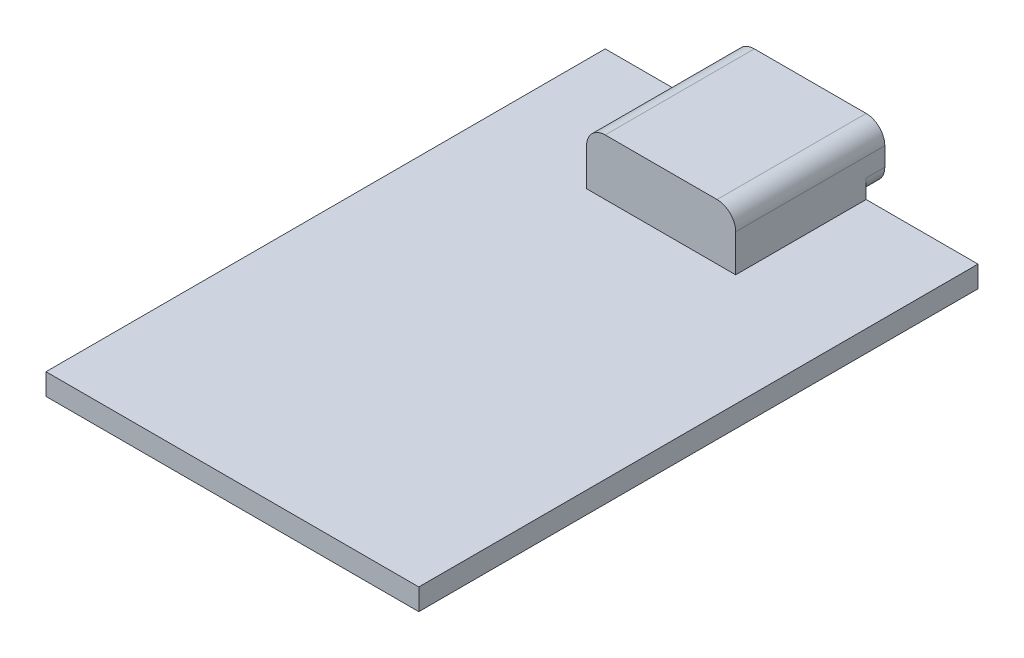
SolidWorks part; units mm, degrees
ref_plane "Alzado" through (0, 0, 0) normal (0, 0, 1) x (1, 0, 0)
ref_plane "Planta" through (0, 0, 0) normal (0, 1, 0) x (1, 0, 0)
ref_plane "Vista lateral" through (0, 0, 0) normal (1, 0, 0) x (0, 0, -1)
sketch "Croquis1" plane through (0, 0, 0) normal (0, 1, 0) x (1, 0, 0)
  line L0 (0, 0) -> (0, 15) construction
  line L1 (-10, 15) -> (10, 15)
  line L2 (-10, 15) -> (-10, -15)
  line L3 (-10, -15) -> (10, -15)
  line L4 (10, 15) -> (10, -15)
  line L5 (-10, 15) -> (10, -15) construction
  line L6 (-10, -15) -> (10, 15) construction
  line L7 (0, 0) -> (-10, 0) construction
  point P0 (0, 0)
  dimension "D1" = 30
  dimension "D2" = 20
extrude "Saliente-Extruir1" add sketch "Croquis1" along normal blind 1.15
sketch "Croquis2" plane through (0, 1.15, 0) normal (0, 1, 0) x (1, 0, 0)
  line L0 (0, 0) -> (0, 12) construction
  line L1 (4, 8) -> (-4, 8)
  line L2 (4, 8) -> (4, 16)
  line L3 (4, 16) -> (-4, 16)
  line L4 (-4, 8) -> (-4, 16)
  line L5 (4, 8) -> (-4, 16) construction
  line L6 (4, 16) -> (-4, 8) construction
  point P0 (0, 12)
  dimension "D1" = 8
  dimension "D2" = 8
  dimension "D3" = 12
extrude "Saliente-Extruir2" add sketch "Croquis2" along normal blind 3
fillet "Redondeo1" radius 1 4 edges at (4, 1.15, -15.5) (-4, 1.15, -15.5) (4, 4.15, -12) (-4, 4.15, -12)
